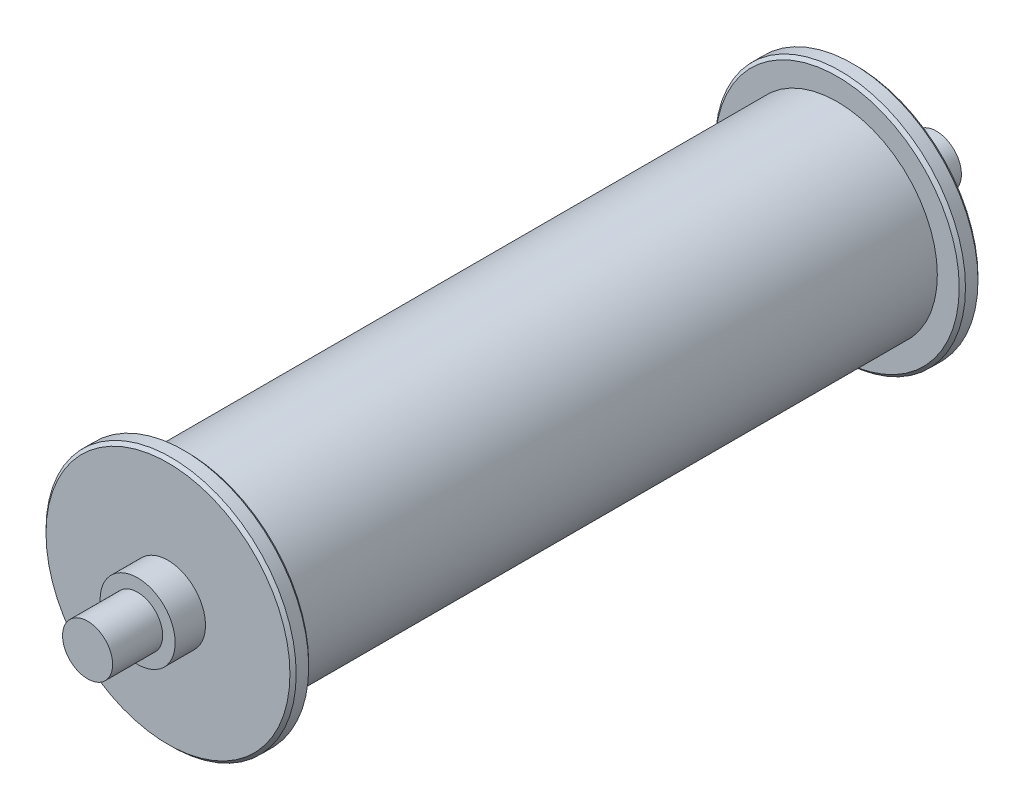
SolidWorks part; units mm, degrees
ref_plane "Front Plane" through (0, 0, 0) normal (0, 0, 1) x (1, 0, 0)
ref_plane "Top Plane" through (0, 0, 0) normal (0, 1, 0) x (1, 0, 0)
ref_plane "Right Plane" through (0, 0, 0) normal (1, 0, 0) x (0, 0, -1)
sketch "Sketch1" plane through (0, 0, 0) normal (0, 0, 1) x (1, 0, 0)
  circle A0 centre (0, 0) radius 20
  dimension "D1" = 40
extrude "Boss-Extrude1" add sketch "Sketch1" along normal blind 3
chamfer "Chamfer1" distance 0.5 angle 45 2 edges at (20, 0, 0) (20, 0, 3)
sketch "Sketch2" plane through (0, 0, 3) normal (0, 0, 1) x (1, 0, 0)
  circle A0 centre (0, 0) radius 16
  dimension "D1" = 32
extrude "Boss-Extrude2" add sketch "Sketch2" along normal blind 104
sketch "Sketch3" plane through (0, 0, 107) normal (0, 0, 1) x (1, 0, 0)
  circle A0 centre (0, 0) radius 20
  dimension "D1" = 40
extrude "Boss-Extrude3" add sketch "Sketch3" along normal blind 3
chamfer "Chamfer2" distance 0.5 angle 45 2 edges at (20, 0, 110) (20, 0, 107)
sketch "Sketch4" plane through (0, 0, 0) normal (0, 0, -1) x (-1, 0, 0)
  circle A0 centre (0, 0) radius 6
  dimension "D1" = 12
extrude "Boss-Extrude4" add sketch "Sketch4" along normal blind 4.85
sketch "Sketch5" plane through (0, 0, -4.85) normal (0, 0, -1) x (-1, 0, 0)
  circle A0 centre (0, 0) radius 4
  dimension "D1" = 8
extrude "Boss-Extrude5" add sketch "Sketch5" along normal blind 8 contours A0
ref_plane "Plane1" through (0, 0, 55) normal (0, 0, -1) x (-1, 0, 0)
mirror "Mirror2" about plane through (0, 0, 55) normal (0, 0, -1) of "Boss-Extrude4", "Boss-Extrude5"
